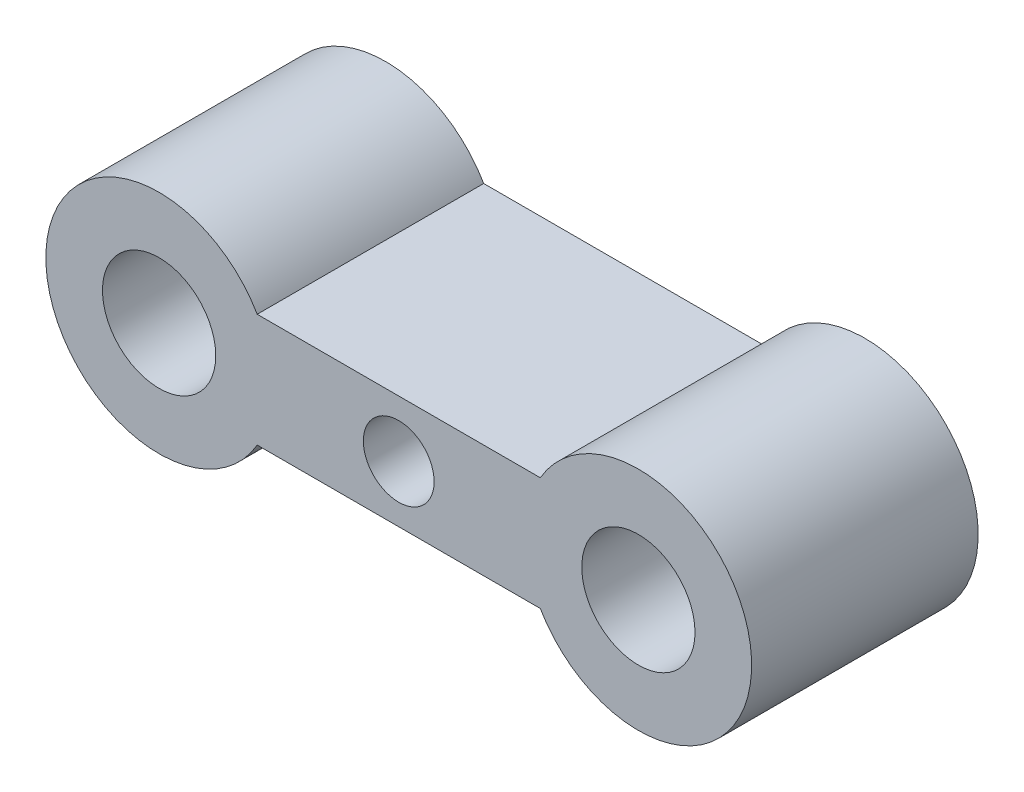
SolidWorks part; units mm, degrees
ref_plane "Alzado" through (0, 0, 0) normal (0, 0, 1) x (1, 0, 0)
ref_plane "Planta" through (0, 0, 0) normal (0, 1, 0) x (1, 0, 0)
ref_plane "Vista lateral" through (0, 0, 0) normal (1, 0, 0) x (0, 0, -1)
sketch "Croquis1" plane through (0, 0, 0) normal (0, 0, 1) x (1, 0, 0)
  line L0 (3.4641, 2) -> (13.4641, 2)
  line L1 (3.4641, -2) -> (13.4641, -2)
  line L2 (8.4641, -2) -> (8.4641, 2)
  circle A0 centre (0, 0) radius 2
  circle A1 centre (0, 0) radius 4
  circle A2 centre (16.9282, 0) radius 2
  circle A3 centre (16.9282, 0) radius 4
  dimension "D1" = 4
  dimension "D3" = 5
  dimension "D2" = 2
extrude "Saliente-Extruir1" add sketch "Croquis1" along normal blind 8 contours A1 A0 | A1 L1 L2 L0 | L1 A3 L0 L2 | A3 A2
sketch "Croquis3" plane through (0, 0, 0) normal (0, 0, -1) x (-1, 0, 0)
  line L0 (-8.4641, 2) -> (-8.4641, -2) construction
  line L1 (-3.4641, 2) -> (-13.4641, 2) construction
  line L2 (-3.4641, -2) -> (-13.4641, -2) construction
  circle A0 centre (-8.4641, 0) radius 1.25
  dimension "D1" = 2.5
extrude "Cortar-Extruir1" cut sketch "Croquis3" against normal blind 21.5
